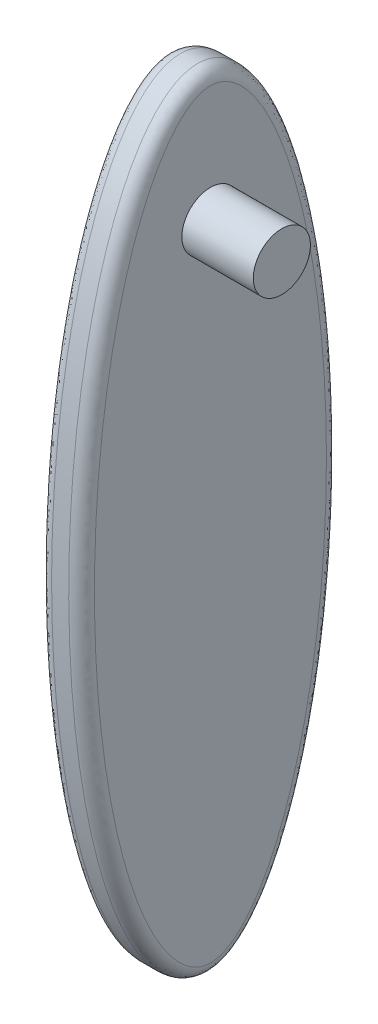
SolidWorks part; units mm, degrees
ref_plane "Front Plane" through (0, 0, 0) normal (0, 0, 1) x (1, 0, 0)
ref_plane "Top Plane" through (0, 0, 0) normal (0, 1, 0) x (1, 0, 0)
ref_plane "Right Plane" through (0, 0, 0) normal (1, 0, 0) x (0, 0, -1)
sketch "Sketch2" plane through (0, 0, 0) normal (1, 0, 0) x (0, 0, -1)
  ellipse E0 centre (0, 0) end of major axis (0, -27.4893) minor radius 9.0202
  point P1 (0, 21.9167)
  point P7 (9.0202, 0)
  point P9 (0, -27.4893)
extrude "Boss-Extrude2" add sketch "Sketch2" along normal blind 3
fillet "Fillet2" radius 0.9 2 edges at (3, -27.4893, 0) (0, -27.4893, 0)
sketch "Sketch3" plane through (0, 0, 0) normal (1, 0, 0) x (0, 0, -1)
  line L0 (0, 15.664) -> (0, -17.9415) construction
  circle A0 centre (0, 18.4269) radius 2
  point P5 (0, 18.4269)
  dimension "D1" = 4
extrude "Boss-Extrude3" add sketch "Sketch3" along normal blind 8
